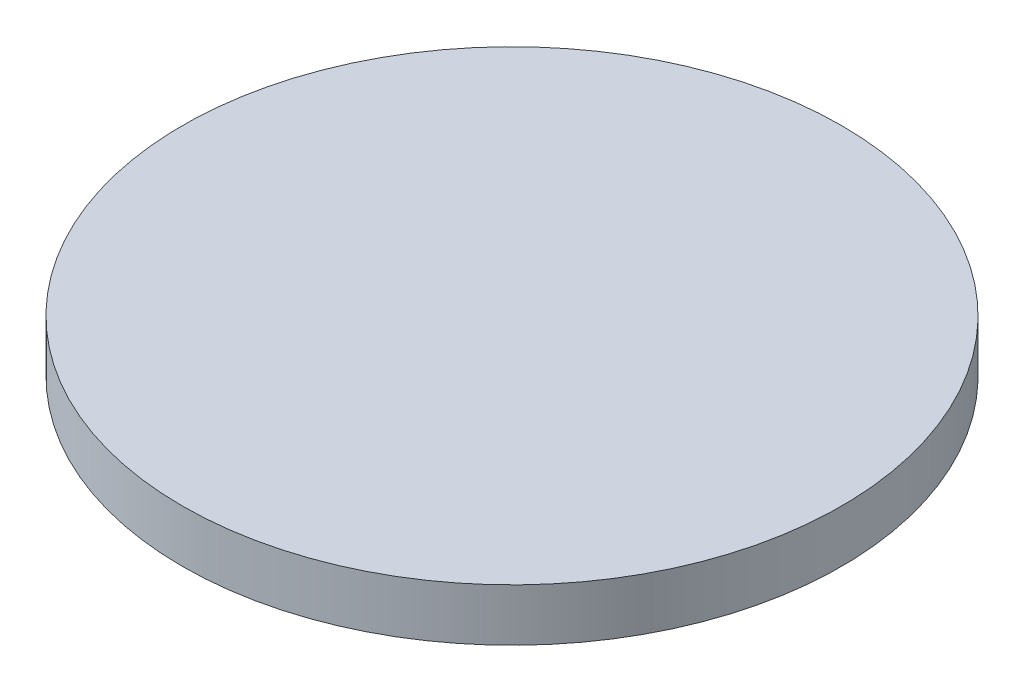
SolidWorks part; units mm, degrees
material "ABS"
ref_plane "Plan de face" through (0, 0, 0) normal (0, 0, 1) x (1, 0, 0)
ref_plane "Plan de dessus" through (0, 0, 0) normal (0, 1, 0) x (1, 0, 0)
ref_plane "Plan de droite" through (0, 0, 0) normal (1, 0, 0) x (0, 0, -1)
sketch "Esquisse1" plane through (0, 0, 0) normal (0, 1, 0) x (1, 0, 0)
  circle A0 centre (0, 0) radius 40
  dimension "D1" = 80
extrude "Boss.-Extru.1" add sketch "Esquisse1" along normal blind 6.35
